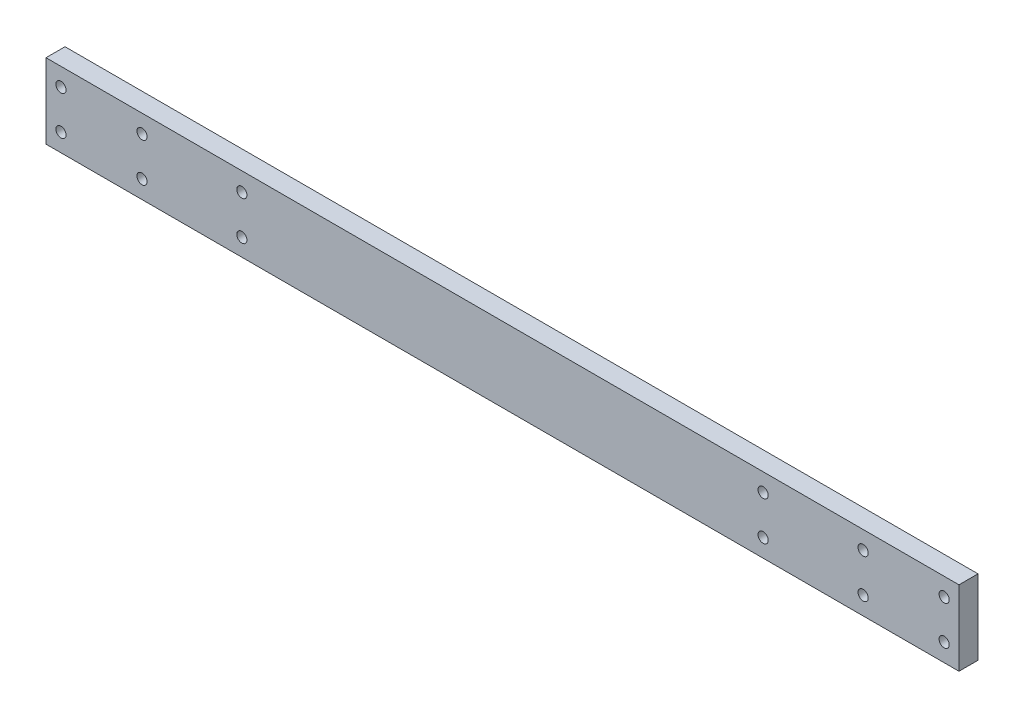
SolidWorks part; units mm, degrees
material "Balsa"
ref_plane "Front Plane" through (0, 0, 0) normal (0, 0, 1) x (1, 0, 0)
ref_plane "Top Plane" through (0, 0, 0) normal (0, 1, 0) x (1, 0, 0)
ref_plane "Right Plane" through (0, 0, 0) normal (1, 0, 0) x (0, 0, -1)
sketch "Sketch1" plane through (0, 0, 0) normal (0, 0, 1) x (1, 0, 0)
  line L1 (-40.7762, 235.9236) -> (264.0238, 235.9236)
  line L2 (-40.7762, 235.9236) -> (-40.7762, 210.9236)
  line L3 (-40.7762, 210.9236) -> (264.0238, 210.9236)
  line L4 (-40.7762, 235.9236) -> (-40.7762, -68.8764)
  line L5 (-40.7762, -68.8764) -> (264.0238, -68.8764)
  line L6 (264.0238, -68.8764) -> (264.0238, 235.9236)
  line L7 (264.0238, 235.9236) -> (-40.7762, 235.9236)
  line L11 (264.0238, 235.9236) -> (-40.7762, 235.9236)
  line L12 (264.0238, 235.9236) -> (264.0238, 210.9236)
  dimension "D1" = 0
extrude "Boss-Extrude1" add sketch "Sketch1" along normal blind 6.35 contours L12 L1 L2 L3
sketch "Sketch2" plane through (0, 0, 6.35) normal (0, 0, 1) x (1, 0, 0)
  circle A0 centre (-8.7262, 216.9236) radius 1.7 construction
  circle A1 centre (-35.7762, 216.9236) radius 1.7
  circle A2 centre (-35.7762, 216.9236) radius 1.7
  circle A3 centre (-35.7762, 229.9236) radius 1.7 construction
  circle A4 centre (-8.7262, 216.9236) radius 1.7
  circle A5 centre (-35.7762, 229.9236) radius 1.7
  circle A6 centre (-8.7262, 229.9236) radius 1.7 construction
  circle A7 centre (-8.7262, 229.9236) radius 1.7
  circle A8 centre (232.0238, 216.9236) radius 1.7 construction
  circle A9 centre (232.0238, 229.9236) radius 1.7 construction
  circle A10 centre (259.0738, 216.9236) radius 1.7 construction
  circle A11 centre (259.0738, 229.9236) radius 1.7 construction
  circle A12 centre (232.0238, 216.9236) radius 1.7
  circle A13 centre (232.0238, 229.9236) radius 1.7
  circle A14 centre (259.0738, 216.9236) radius 1.7
  circle A15 centre (259.0738, 229.9236) radius 1.7
  dimension "D1" = 0
extrude "Cut-Extrude1" cut sketch "Sketch2" against normal blind 10
sketch "Sketch3" plane through (0, 0, 6.35) normal (0, 0, 1) x (1, 0, 0)
  circle A0 centre (24.6101, 229.7193) radius 1.7 construction
  circle A1 centre (24.6101, 216.7193) radius 1.7 construction
  circle A2 centre (198.6375, 216.9236) radius 1.7 construction
  circle A3 centre (198.6375, 229.9236) radius 1.7 construction
  circle A4 centre (24.6101, 229.7193) radius 1.7
  circle A5 centre (24.6101, 216.7193) radius 1.7
  circle A6 centre (198.6375, 216.9236) radius 1.7
  circle A7 centre (198.6375, 229.9236) radius 1.7
extrude "Cut-Extrude2" cut sketch "Sketch3" against normal blind 21
